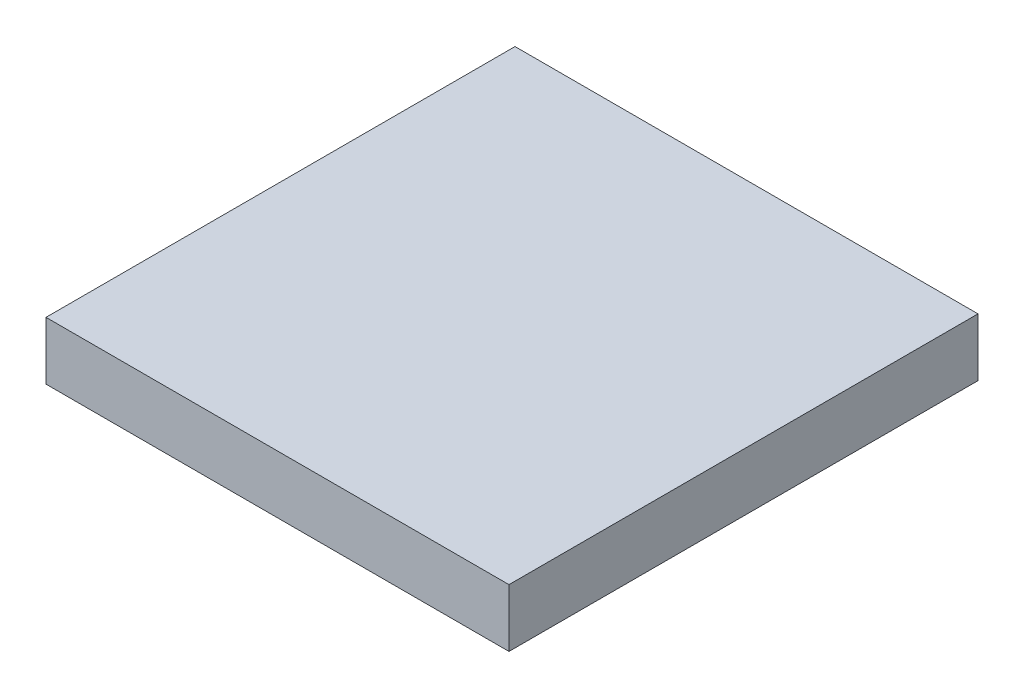
SolidWorks part; units mm, degrees
material "POLYURETHANE (11671)"
ref_plane "Front Plane" through (0, 0, 0) normal (0, 0, 1) x (1, 0, 0)
ref_plane "Top Plane" through (0, 0, 0) normal (0, 1, 0) x (1, 0, 0)
ref_plane "Right Plane" through (0, 0, 0) normal (1, 0, 0) x (0, 0, -1)
sketch "Sketch1" plane through (0, 0, 0) normal (0, 1, 0) x (1, 0, 0)
  line L1 (-12.7, 12.8657) -> (12.7, 12.8657)
  line L2 (-12.7, 12.8657) -> (-12.7, -12.8657)
  line L3 (-12.7, -12.8657) -> (12.7, -12.8657)
  line L4 (12.7, 12.8657) -> (12.7, -12.8657)
  line L5 (-12.7, 12.8657) -> (12.7, -12.8657) construction
  line L6 (-12.7, -12.8657) -> (12.7, 12.8657) construction
  point P0 (0, 0)
  point P5 (2.8713, -3.6996)
  point P6 (18.9948, -20.817)
  point P7 (0, 0)
  point P8 (0, 0)
  dimension "D1" = 25.4
  dimension "D2" = 25.7313
extrude "Boss-Extrude1" add sketch "Sketch1" along normal blind 3.175
